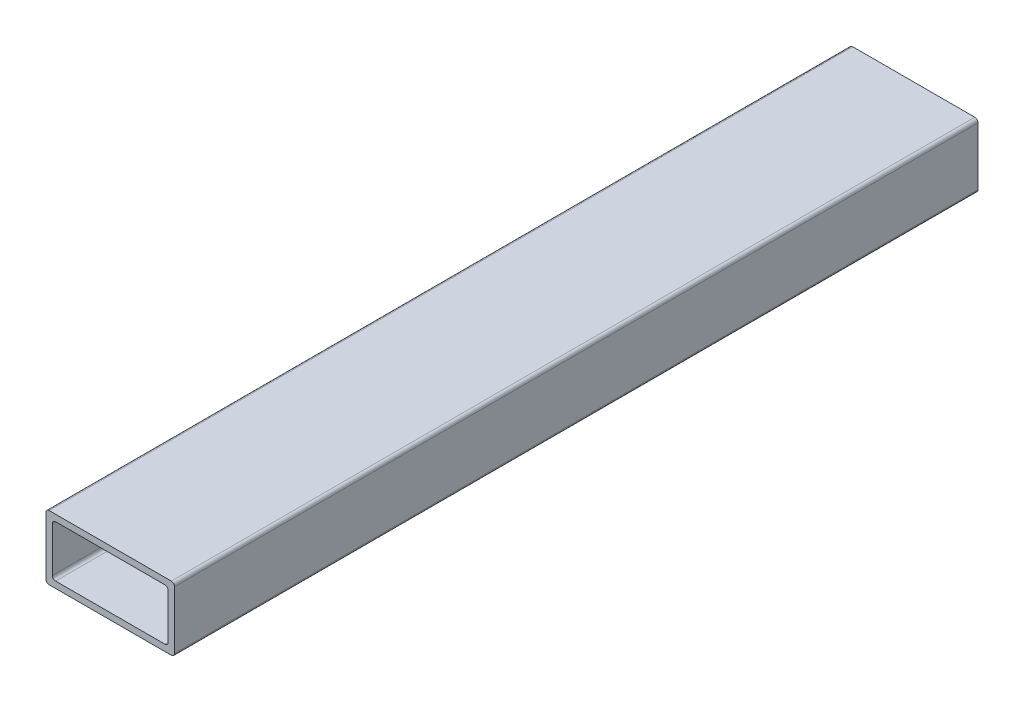
SolidWorks part; units mm, degrees
ref_plane "Plan de face" through (0, 0, 0) normal (0, 0, 1) x (1, 0, 0)
ref_plane "Plan de dessus" through (0, 0, 0) normal (0, 1, 0) x (1, 0, 0)
ref_plane "Plan de droite" through (0, 0, 0) normal (1, 0, 0) x (0, 0, -1)
sketch "Esquisse2" plane through (0, 0, 0) normal (0, 0, 1) x (1, 0, 0)
  line L0 (6, 4) -> (74, 4)
  line L1 (2, 0) -> (78, 0)
  line L2 (0, 2) -> (0, 38)
  line L3 (2, 40) -> (78, 40)
  line L4 (80, 2) -> (80, 38)
  line L5 (76, 6) -> (76, 34)
  line L6 (6, 36) -> (74, 36)
  line L7 (4, 6) -> (4, 34)
  line L8 (4, 4) -> (76, 4) construction
  line L9 (76, 4) -> (76, 36) construction
  line L10 (4, 36) -> (76, 36) construction
  line L11 (4, 4) -> (4, 36) construction
  line L12 (0, 0) -> (80, 0) construction
  line L13 (0, 0) -> (0, 40) construction
  line L14 (0, 40) -> (80, 40) construction
  line L15 (80, 0) -> (80, 40) construction
  arc A0 (74, 4) -> (76, 6) centre (74, 6) ccw
  arc A1 (76, 34) -> (74, 36) centre (74, 34) ccw
  arc A2 (6, 36) -> (4, 34) centre (6, 34) ccw
  arc A3 (4, 6) -> (6, 4) centre (6, 6) ccw
  arc A4 (2, 0) -> (0, 2) centre (2, 2) cw
  arc A5 (0, 38) -> (2, 40) centre (2, 38) cw
  arc A6 (78, 40) -> (80, 38) centre (78, 38) cw
  arc A7 (80, 2) -> (78, 0) centre (78, 2) cw
  point P24 (0, 0)
  dimension "D4" = 2
  dimension "D1" = 40
  dimension "D2" = 80
  dimension "D3" = 4
extrude "Boss.-Extru.1" add sketch "Esquisse2" along normal blind 500
